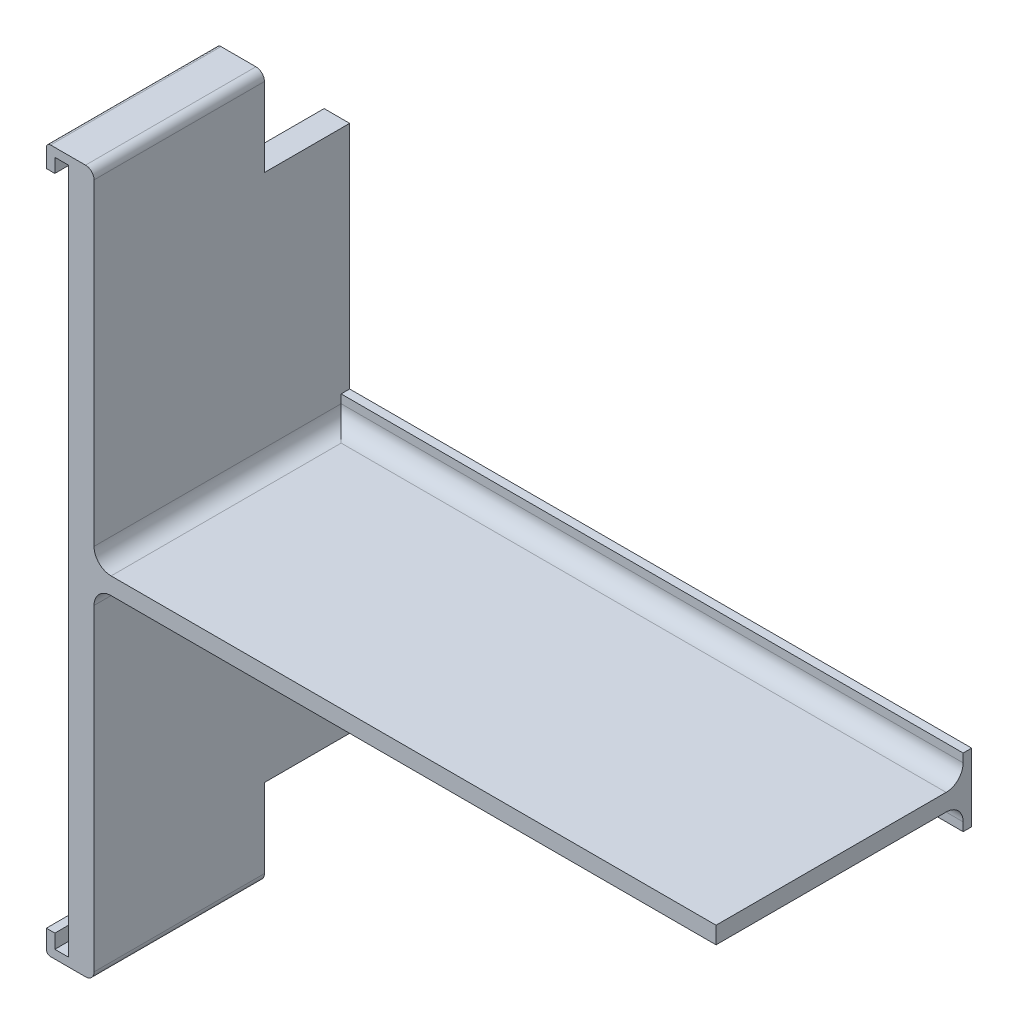
SolidWorks part; units mm, degrees
ref_plane "Front Plane" through (0, 0, 0) normal (1, 0, 0) x (0, 1, 0)
ref_plane "Top Plane" through (0, 0, 0) normal (0, 0, 1) x (0, 1, 0)
ref_plane "Right Plane" through (0, 0, 0) normal (0, 1, 0) x (-1, 0, 0)
sketch "Sketch1" plane through (0, 0, 0) normal (0, 0, 1) x (0, 1, 0)
  line L0 (-41.25, 1.8) -> (-38.6035, 1.8)
  line L9 (-40.25, -0.8) -> (40.25, -0.8)
  line L10 (-40.25, -0.8) -> (-40.25, 0.8)
  line L11 (-40.25, 0.8) -> (-38.6035, 0.8)
  line L12 (40.25, -0.8) -> (40.25, 0.8)
  line L13 (-40.25, -0.8) -> (40.25, 0.8) construction
  line L14 (-40.25, 0.8) -> (40.25, -0.8) construction
  line L15 (41.25, -3.8) -> (41.25, 1.8)
  line L17 (-41.25, -3.8) -> (-41.25, 1.8)
  line L18 (-38.6035, 1.8) -> (-38.6035, 0.8)
  line L19 (-41.25, -1.8) -> (41.25, -1.8) construction
  line L20 (-41.25, -3.8) -> (58.7943, -3.8)
  line L21 (-41.25, -1.8) -> (-41.25, 1.8) construction
  line L22 (41.25, -1.8) -> (41.25, 1.8) construction
  line L23 (0, 0) -> (0, 5.565) construction
  line L24 (38.6035, 1.8) -> (38.6035, 0.8)
  line L25 (38.6035, 1.8) -> (41.25, 1.8)
  line L26 (-41.25, 1.8) -> (41.25, 1.8) construction
  line L27 (38.6035, 0.8) -> (40.25, 0.8)
  line L28 (-38.6035, -0.7673) -> (-38.6035, -0.8)
  line L29 (-40.25, 0.8) -> (40.25, 0.8) construction
  point P0 (0, 0)
  dimension "D1" = 80.5
  dimension "D2" = 1.6
  dimension "D3" = 1.6465
  dimension "D4" = 1
  dimension "D5" = 3
extrude "Boss-Extrude1" add sketch "Sketch1" along normal blind 20 contours L24 L27 L12 L9 L10 L11 L18 L0 L17 L20 L15 L25
sketch "Sketch3" plane through (0, 0, 20) normal (0, 0, 1) x (1, 0, 0)
  line L0 (0.8, 0) -> (65.1581, 0) construction
  line L1 (0.8, -40.25) -> (0.8, 40.25) construction
  line L3 (0.8, -1) -> (76.8, -1)
  line L4 (0.8, -1) -> (0.8, 1)
  line L5 (0.8, 1) -> (76.8, 1)
  line L6 (76.8, -1) -> (76.8, 1)
  dimension "D1" = 2
  dimension "D2" = 1
  dimension "D3" = 76
extrude "Boss-Extrude2" add sketch "Sketch3" against normal blind 30
fillet "Fillet2" radius 1 2 edges at (3.8, 41.25, 10) (3.8, -41.25, 10)
fillet "Fillet3" radius 0.5 2 edges at (-1.8, 41.25, 10) (-1.8, -41.25, 10)
sketch "Sketch4" plane through (0, 0, 0) normal (0, 0, -1) x (1, 0, 0)
  line L0 (0.8, -1) -> (0.8, -40.25) construction
  line L1 (0.8, -31) -> (3.8, -31)
  line L2 (0.8, -31) -> (0.8, 31)
  line L3 (0.8, 31) -> (3.8, 31)
  line L4 (3.8, -31) -> (3.8, 31)
  line L5 (3.8, 40.25) -> (3.8, 1) construction
  line L6 (0.8, 1) -> (76.8, 1) construction
  line L7 (76.8, -1) -> (0.8, -1) construction
  dimension "D1" = 30
  dimension "D2" = 30
extrude "Boss-Extrude3" add sketch "Sketch4" along normal up to surface (10 mm away) up to face at (38.8, 0, -10)
sketch "Sketch5" plane through (0, 0, -10) normal (0, 0, -1) x (1, 0, 0)
  line L0 (0.8, -31) -> (0.8, 31) construction
  line L1 (0.8, 4) -> (76.8, 4)
  line L2 (0.8, 4) -> (0.8, -4)
  line L3 (0.8, -4) -> (76.8, -4)
  line L4 (76.8, 4) -> (76.8, -4)
  line L5 (3.8, 1) -> (76.8, 1) construction
  line L6 (76.8, -1) -> (3.8, -1) construction
  dimension "D1" = 3
  dimension "D2" = 3
extrude "Boss-Extrude4" add sketch "Sketch5" against normal blind 1
fillet "Fillet5" radius 2 4 edges at (3.8, -1, 5.5) (40.3, -1, -9) (40.3, 1, -9) (3.8, 1, 5.5)
